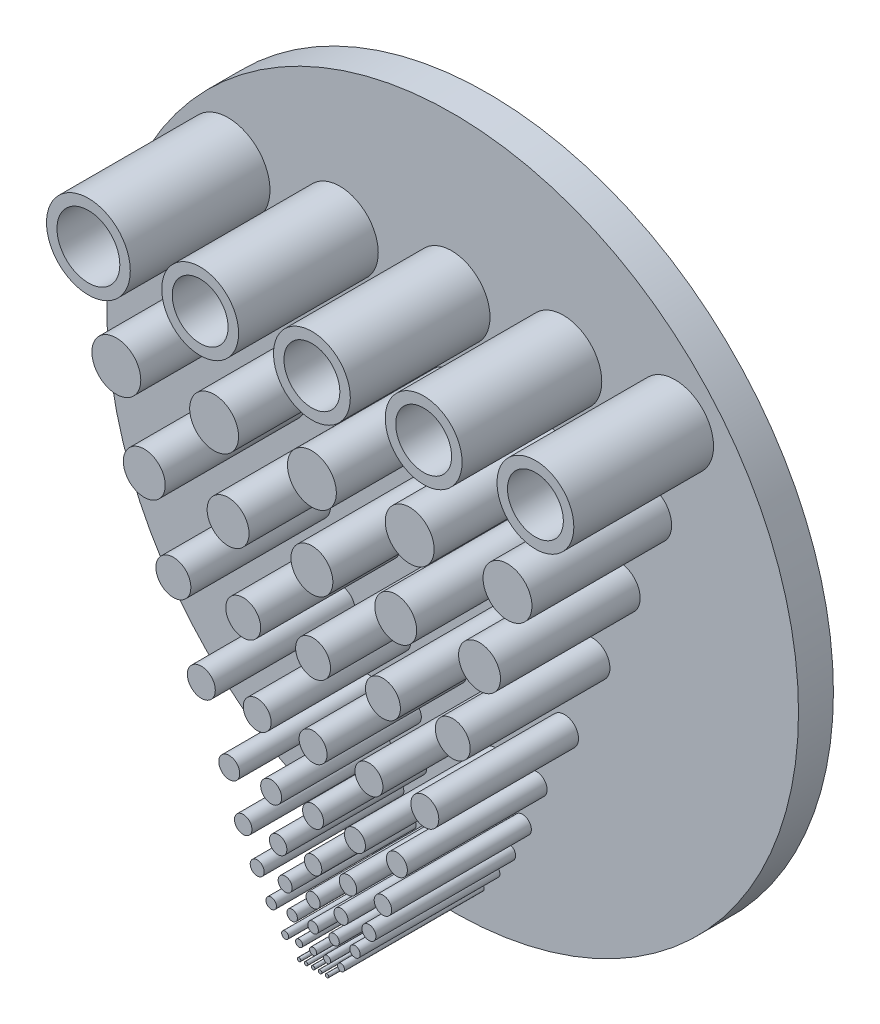
SolidWorks part; units mm, degrees
ref_plane "Front Plane" through (0, 0, 0) normal (0, 0, 1) x (1, 0, 0)
ref_plane "Top Plane" through (0, 0, 0) normal (0, 1, 0) x (1, 0, 0)
ref_plane "Right Plane" through (0, 0, 0) normal (1, 0, 0) x (0, 0, -1)
sketch "Sketch1" plane through (0, 0, 0) normal (0, 0, 1) x (1, 0, 0)
  line L0 (0, 0) -> (0, -47.5) construction
  line L1 (-10, -46.4354) -> (10, -46.4354) construction
  line L2 (-38.9101, 2.7897) -> (38.5749, 2.7897) construction
  line L3 (-2.25, -46.4354) -> (2.25, -46.4354) construction
  line L4 (-5.1096, -44.4008) -> (5.1096, -44.4008) construction
  line L5 (-7.7103, -38.0667) -> (7.7103, -38.0667) construction
  line L6 (-17.0594, -27.6226) -> (17.0594, -27.6226) construction
  line L7 (2, 0) -> (2, -47.5) construction
  line L8 (4, 0) -> (4, -47.5) construction
  line L9 (-22.023, -19.0448) -> (22.023, -19.0448) construction
  line L10 (-36.0811, -8.0429) -> (36.0811, -8.0429) construction
  line L11 (-38.9101, 14.0714) -> (38.5749, 14.0714) construction
  line L12 (-39.1649, 26.8768) -> (38.8297, 26.8768) construction
  line L13 (-16, -33.679) -> (16, -33.679) construction
  line L14 (-9.4192, -41.4393) -> (9.4192, -41.4393) construction
  line L15 (-9.4192, -41.4393) -> (-20.9544, -41.4393) construction
  circle A0 centre (0, 0) radius 47.5 construction
  circle A1 centre (0, -46.4354) radius 0.25
  circle A2 centre (1, -46.4354) radius 0.25
  circle A3 centre (2, -46.4354) radius 0.25
  circle A4 centre (-1, -46.4354) radius 0.25
  circle A5 centre (-2, -46.4354) radius 0.25
  circle A6 centre (0, -44.4008) radius 0.5
  circle A7 centre (2, -44.4008) radius 0.5
  circle A8 centre (4, -44.4008) radius 0.5
  circle A9 centre (-2, -44.4008) radius 0.5
  circle A10 centre (-4, -44.4008) radius 0.5
  circle A11 centre (0, -38.0667) radius 1
  circle A12 centre (4, -38.0667) radius 1
  circle A13 centre (8, -38.0667) radius 1
  circle A14 centre (-4, -38.0667) radius 1
  circle A15 centre (-8, -38.0667) radius 1
  circle A16 centre (0, -27.6226) radius 1.5
  circle A17 centre (6, -27.6226) radius 1.5
  circle A18 centre (12, -27.6226) radius 1.5
  circle A19 centre (-6, -27.6226) radius 1.5
  circle A20 centre (-12, -27.6226) radius 1.5
  circle A21 centre (0, -19.0448) radius 2
  circle A22 centre (8, -19.0448) radius 2
  circle A23 centre (16, -19.0448) radius 2
  circle A24 centre (-8, -19.0448) radius 2
  circle A25 centre (-16, -19.0448) radius 2
  circle A26 centre (0, -8.0429) radius 2.5
  circle A27 centre (10, -8.0429) radius 2.5
  circle A28 centre (20, -8.0429) radius 2.5
  circle A29 centre (-10, -8.0429) radius 2.5
  circle A30 centre (-20, -8.0429) radius 2.5
  circle A31 centre (-0.1676, 2.7897) radius 3
  circle A32 centre (11.8324, 2.7897) radius 3
  circle A33 centre (23.8324, 2.7897) radius 3
  circle A34 centre (-12.1676, 2.7897) radius 3
  circle A35 centre (-24.1676, 2.7897) radius 3
  circle A36 centre (-0.1676, 14.0714) radius 3.5
  circle A41 centre (13.8324, 14.0714) radius 3.5
  circle A42 centre (27.8324, 14.0714) radius 3.5
  circle A43 centre (-14.1676, 14.0714) radius 3.5
  circle A44 centre (-28.1676, 14.0714) radius 3.5
  circle A45 centre (-0.1676, 26.8768) radius 4
  circle A48 centre (15.8324, 26.8768) radius 4
  circle A49 centre (31.8324, 26.8768) radius 4
  circle A50 centre (-16.1676, 26.8768) radius 4
  circle A51 centre (-32.1676, 26.8768) radius 4
  circle A52 centre (0, -33.679) radius 1.25
  circle A53 centre (5, -33.679) radius 1.25
  circle A54 centre (10, -33.679) radius 1.25
  circle A55 centre (-5, -33.679) radius 1.25
  circle A56 centre (-10, -33.679) radius 1.25
  circle A57 centre (0, -41.4393) radius 0.75
  circle A58 centre (-3, -41.4393) radius 0.75
  circle A59 centre (-6, -41.4393) radius 0.75
  circle A60 centre (3, -41.4393) radius 0.75
  circle A61 centre (6, -41.4393) radius 0.75
  point P9 (-20.9544, -41.4393)
  point P12 (0, -33.679)
  point P30 (0, -44.4008)
  point P45 (0, -38.0667)
  point P58 (0, -27.6226)
  point P71 (0, -19.0448)
  point P84 (0, -8.0429)
  point P95 (-0.1676, 2.7897)
  point P108 (-0.1676, 16.9936)
  point P121 (-0.1676, 26.8768)
  point P143 (0, -41.4393)
  point P161 (-20.9544, -41.4393)
  dimension "D1" = 95
  dimension "D4" = 0.5
  dimension "D7" = 1
  dimension "D8" = 3
  dimension "D10" = 2
  dimension "D13" = 3
  dimension "D16" = 4
  dimension "D19" = 5
  dimension "D3" = 6
  dimension "D24" = 7
  dimension "D27" = 8
  dimension "D30" = 2.5
  dimension "D33" = 1.5
  dimension "D2" = 20
  dimension "D14" = 3
  dimension "D31" = 3
  dimension "D5" = 3
  dimension "D6" = 3
  dimension "D9" = 3
  dimension "D11" = 3
  dimension "D12" = 3
  dimension "D15" = 3
  dimension "D17" = 3
  dimension "D18" = 3
  dimension "D20" = 3
  dimension "D21" = 3
  dimension "D22" = 3
  dimension "D23" = 3
  dimension "D25" = 3
  dimension "D26" = 3
  dimension "D28" = 3
  dimension "D29" = 3
  dimension "D32" = 3
  dimension "D34" = 3
  dimension "D35" = 3
extrude "Boss-Extrude1" add sketch "Sketch1" along normal blind 20
sketch "Sketch4" plane through (0, 0, 0) normal (0, 0, 1) x (1, 0, 0)
  circle A0 centre (0, 0) radius 49.5
  dimension "D1" = 99
extrude "Boss-Extrude2" add sketch "Sketch4" against normal blind 5
sketch "Sketch6" plane through (0, 0, 20) normal (0, 0, 1) x (1, 0, 0)
  circle A2 centre (-16.1676, 26.8768) radius 5.5
  circle A3 centre (-16.1676, 26.8768) radius 5.5
  circle A8 centre (-0.1676, 26.8768) radius 5.5
  circle A9 centre (-0.1676, 26.8768) radius 5.5
  circle A11 centre (15.8324, 26.8768) radius 5.5
  circle A12 centre (15.8324, 26.8768) radius 5.5
  circle A13 centre (-32.1676, 26.8768) radius 4 construction
  circle A14 centre (31.8324, 26.8768) radius 5.5
  circle A15 centre (31.8324, 26.8768) radius 5.5
  circle A16 centre (-32.1676, 26.8768) radius 6
  circle A17 centre (-32.1676, 26.8768) radius 6
  circle A18 centre (-32.1676, 26.8768) radius 4
  circle A19 centre (-16.1676, 26.8768) radius 4 construction
  circle A20 centre (-16.1676, 26.8768) radius 4
  circle A21 centre (-0.1676, 26.8768) radius 4 construction
  circle A22 centre (-0.1676, 26.8768) radius 4
  circle A23 centre (15.8324, 26.8768) radius 4 construction
  circle A24 centre (15.8324, 26.8768) radius 4
  circle A25 centre (31.8324, 26.8768) radius 4 construction
  circle A26 centre (31.8324, 26.8768) radius 4
  dimension "D1" = 1.5
  dimension "D2" = 2
  dimension "D3" = 1.5
  dimension "D4" = 1.5
  dimension "D5" = 1.5
extrude "Boss-Extrude3" add sketch "Sketch6" against normal up to surface (20 mm away) up to face at (6.75, -41.4393, 0)
sketch "Sketch7" plane through (0, 0, 20) normal (0, 0, 1) x (1, 0, 0)
  circle A5 centre (-32.1676, 26.8768) radius 4.5
  circle A6 centre (-32.1676, 26.8768) radius 4.5
  circle A8 centre (-16.1676, 26.8768) radius 4
  circle A9 centre (-16.1676, 26.8768) radius 4
  circle A11 centre (-0.1676, 26.8768) radius 4
  circle A12 centre (-0.1676, 26.8768) radius 4
  circle A14 centre (15.8324, 26.8768) radius 4
  circle A15 centre (15.8324, 26.8768) radius 4
  circle A17 centre (31.8324, 26.8768) radius 4
  circle A18 centre (31.8324, 26.8768) radius 4
  dimension "D1" = 1.5
  dimension "D2" = 1.5
  dimension "D3" = 1.5
  dimension "D4" = 1.5
  dimension "D5" = 1.5
extrude "Cut-Extrude1" cut sketch "Sketch7" against normal up to surface (20 mm away) up to face at (-26.1676, 26.8768, 0)
